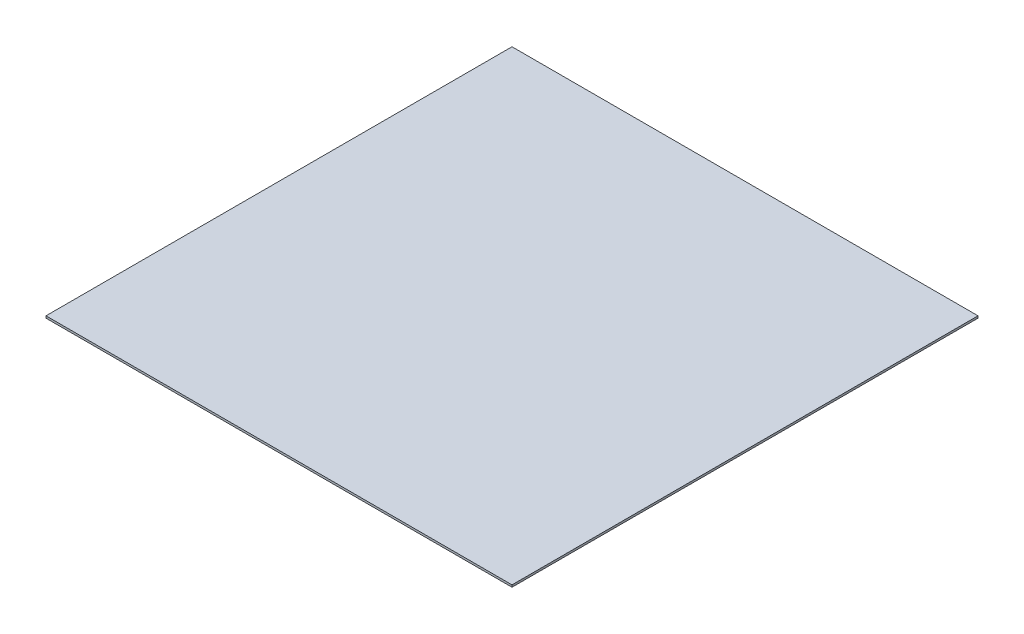
SolidWorks part; units mm, degrees
material "1060 Alloy"
ref_plane "Front Plane" through (0, 0, 0) normal (0, 0, 1) x (1, 0, 0)
ref_plane "Top Plane" through (0, 0, 0) normal (0, 1, 0) x (1, 0, 0)
ref_plane "Right Plane" through (0, 0, 0) normal (1, 0, 0) x (0, 0, -1)
sketch "Sketch1" plane through (0, 0, 0) normal (0, 1, 0) x (1, 0, 0)
  line L1 (337.7346, 267.1998) -> (1048.9346, 267.1998)
  line L2 (337.7346, 267.1998) -> (337.7346, -444.0002)
  line L3 (337.7346, -444.0002) -> (1048.9346, -444.0002)
  line L4 (1048.9346, 267.1998) -> (1048.9346, -444.0002)
extrude "Boss-Extrude1" add sketch "Sketch1" along normal blind 3.175
